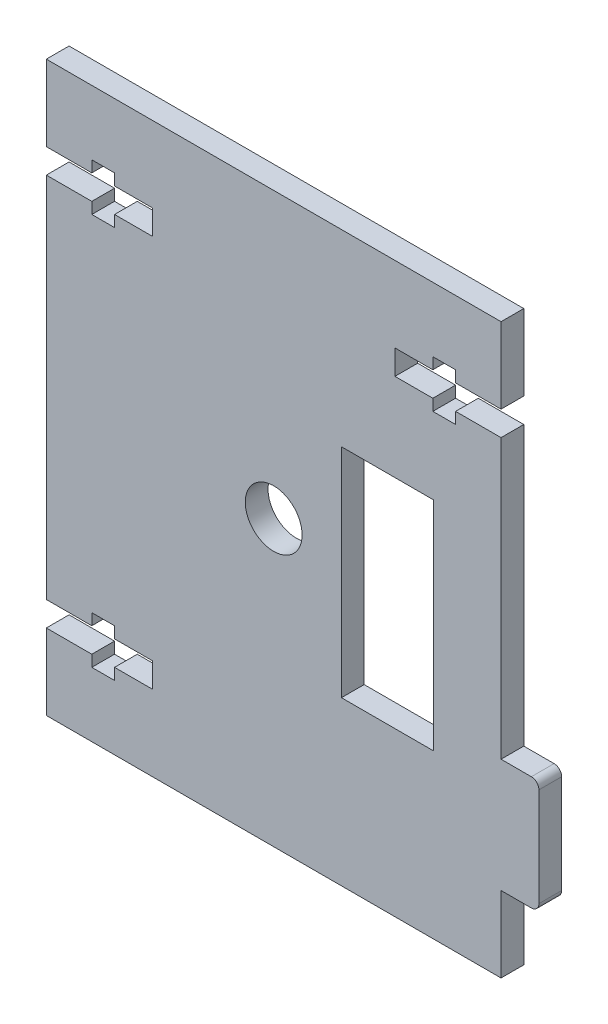
SolidWorks part; units mm, degrees
ref_plane "Front Plane" through (0, 0, 0) normal (0, 0, 1) x (1, 0, 0)
ref_plane "Top Plane" through (0, 0, 0) normal (0, 1, 0) x (1, 0, 0)
ref_plane "Right Plane" through (0, 0, 0) normal (1, 0, 0) x (0, 0, -1)
sketch "Esquisse1" plane through (0, 0, 0) normal (0, 0, 1) x (1, 0, 0)
  line L0 (-30, 37.5) -> (30, 37.5)
  line L1 (30, 37.5) -> (30, 27.5)
  line L2 (30, 27.5) -> (24, 27.5)
  line L3 (24, 27.5) -> (24, 29)
  line L4 (24, 29) -> (21, 29)
  line L5 (30, 12.5) -> (30, -12.5)
  line L6 (30, -12.5) -> (35, -12.5)
  line L7 (35, -12.5) -> (35, -27.5)
  line L8 (35, -27.5) -> (30, -27.5)
  line L9 (30, -27.5) -> (30, -37.5)
  line L10 (30, -37.5) -> (-30, -37.5)
  line L11 (-30, -37.5) -> (-30, -27.5)
  line L12 (-30, -27.5) -> (-24, -27.5)
  line L13 (-24, -27.5) -> (-24, -29)
  line L14 (-24, -29) -> (-21, -29)
  line L15 (-30, -12.5) -> (-30, 12.5)
  line L16 (0, 0) -> (0, 61.721) construction
  line L17 (-24, 24.25) -> (-30, 24.25)
  line L18 (-30, 27.5) -> (-24, 27.5)
  line L19 (-30, 27.5) -> (-30, 37.5)
  line L20 (21, 29) -> (21, 27.5)
  line L21 (8.94, 12.68) -> (21.06, 12.68)
  line L22 (8.94, 12.68) -> (8.94, -16)
  line L23 (8.94, -16) -> (21.06, -16)
  line L24 (21.06, 12.68) -> (21.06, -16)
  line L33 (21, 27.5) -> (16, 27.5)
  line L34 (16, 27.5) -> (16, 24.25)
  line L35 (16, 24.25) -> (21, 24.25)
  line L36 (21, 24.25) -> (21, 22.75)
  line L37 (21, 22.75) -> (24, 22.75)
  line L38 (24, 22.75) -> (24, 24.25)
  line L39 (24, 24.25) -> (30, 24.25)
  line L40 (30, 24.25) -> (30, 12.5)
  line L41 (-21, -29) -> (-21, -27.5)
  line L42 (-21, -27.5) -> (-16, -27.5)
  line L43 (-16, -27.5) -> (-16, -24.25)
  line L44 (-16, -24.25) -> (-21, -24.25)
  line L45 (-21, -24.25) -> (-21, -22.75)
  line L46 (-21, -22.75) -> (-24, -22.75)
  line L47 (-24, -22.75) -> (-24, -24.25)
  line L48 (-24, -24.25) -> (-30, -24.25)
  line L49 (-30, -24.25) -> (-30, -12.5)
  line L50 (-24, 22.75) -> (-24, 24.25)
  line L51 (-21, 22.75) -> (-24, 22.75)
  line L52 (-21, 24.25) -> (-21, 22.75)
  line L53 (-16, 24.25) -> (-21, 24.25)
  line L54 (-16, 27.5) -> (-16, 24.25)
  line L55 (-21, 27.5) -> (-16, 27.5)
  line L56 (-21, 29) -> (-21, 27.5)
  line L57 (-24, 29) -> (-21, 29)
  line L58 (-24, 27.5) -> (-24, 29)
  line L59 (-30, 24.25) -> (-30, 12.5)
  circle A0 centre (0, 0) radius 3.75
  dimension "D28" = 7.5
  dimension "D2" = 60
  dimension "D3" = 60
  dimension "D5" = 60
  dimension "D6" = 3.25
  dimension "D7" = 5
  dimension "D8" = 8.94
  dimension "D9" = 9
  dimension "D10" = 0
  dimension "D11" = 75
  dimension "D12" = 14
  dimension "D14" = 6
  dimension "D15" = 15
  dimension "D16" = 25
  dimension "D17" = 25
  dimension "D18" = 10
  dimension "D19" = 37.5
  dimension "D21" = 12.68
  dimension "D22" = 16
  dimension "D23" = 12.12
  dimension "D33" = 6.25
  dimension "D34" = 1.5
  dimension "D35" = 10
  dimension "D36" = 1.5
  dimension "D37" = 3.25
  dimension "D38" = 6
  dimension "D39" = 9
  dimension "D40" = 14
  dimension "D41" = 3.25
  dimension "D42" = 10
  dimension "D43" = 6
  dimension "D44" = 6
  dimension "D45" = 9
  dimension "D46" = 9
  dimension "D47" = 6.25
  dimension "D48" = 1.5
  dimension "D49" = 3.25
  dimension "D50" = 10
extrude "Boss.-Extru.1" add sketch "Esquisse1" along normal blind 3
fillet "Congé3" radius 1 2 edges at (35, -27.5, 1.5) (35, -12.5, 1.5)
